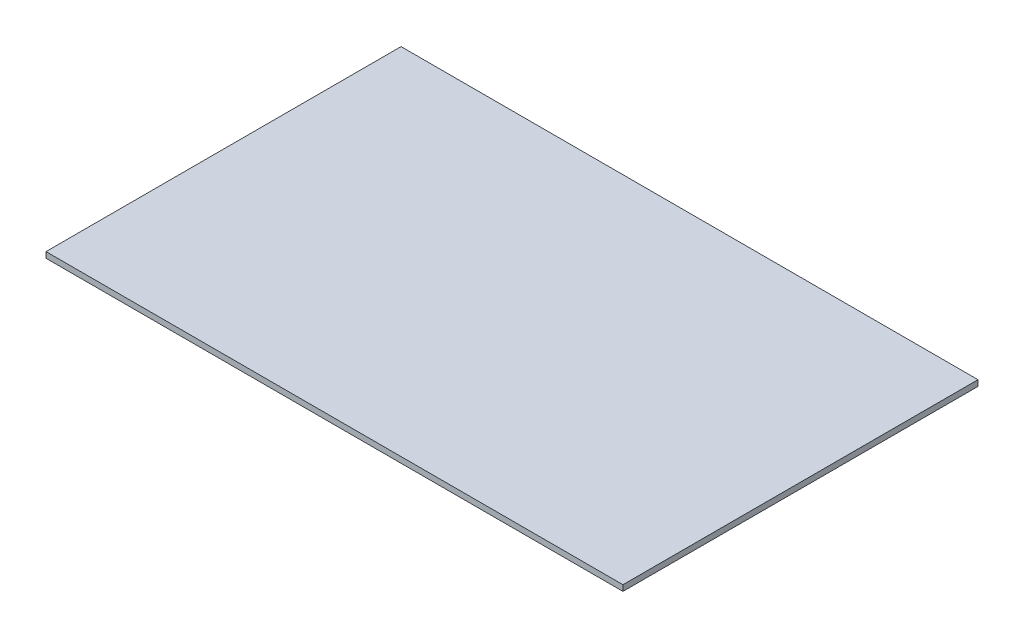
SolidWorks part; units mm, degrees
ref_plane "Front Plane" through (0, 0, 0) normal (0, 0, 1) x (1, 0, 0)
ref_plane "Top Plane" through (0, 0, 0) normal (0, 1, 0) x (1, 0, 0)
ref_plane "Right Plane" through (0, 0, 0) normal (1, 0, 0) x (0, 0, -1)
sketch "Sketch1" plane through (0, 0, 0) normal (0, 1, 0) x (1, 0, 0)
  line L1 (495.3, -304.8) -> (-495.3, -304.8)
  line L2 (495.3, -304.8) -> (495.3, 304.8)
  line L3 (495.3, 304.8) -> (-495.3, 304.8)
  line L4 (-495.3, -304.8) -> (-495.3, 304.8)
  line L5 (495.3, -304.8) -> (-495.3, 304.8) construction
  line L6 (495.3, 304.8) -> (-495.3, -304.8) construction
  point P0 (0, 0)
  dimension "D1" = 990.6
  dimension "D2" = 609.6
extrude "Boss-Extrude1" add sketch "Sketch1" along normal blind 10
